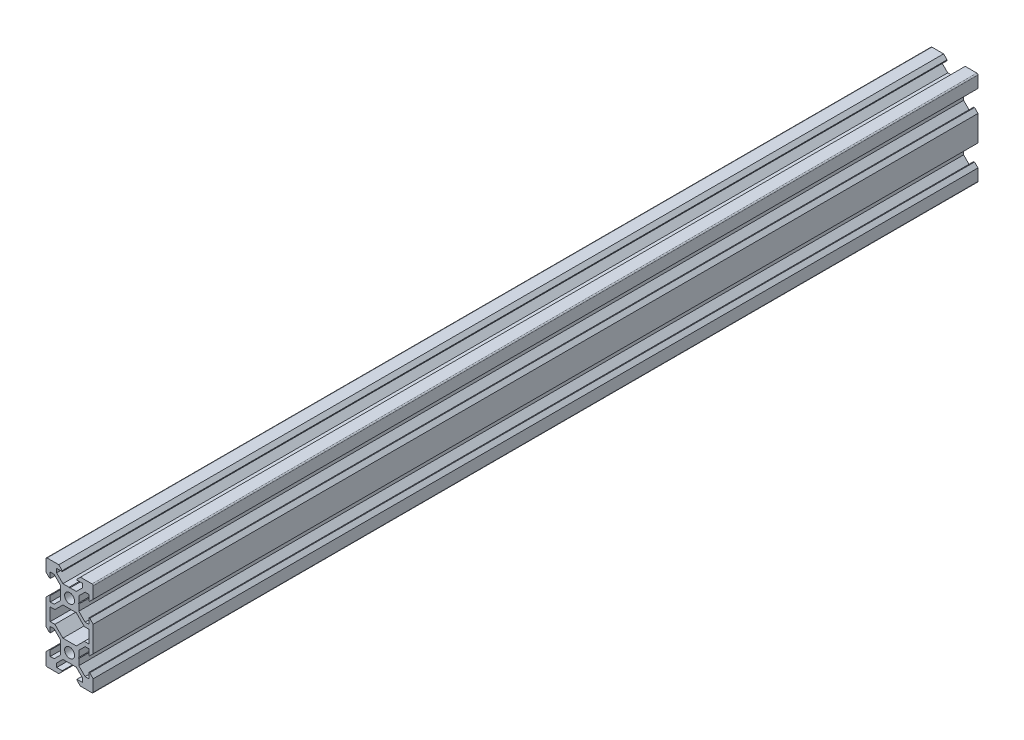
SolidWorks part; units mm, degrees
material "6061-T6 (SS)"
ref_plane "Front Plane" through (0, 0, 0) normal (0, 0, 1) x (1, 0, 0)
ref_plane "Top Plane" through (0, 0, 0) normal (0, 1, 0) x (1, 0, 0)
ref_plane "Right Plane" through (0, 0, 0) normal (1, 0, 0) x (0, 0, -1)
sketch "Sketch1" plane through (0, 0, 0) normal (0, 0, 1) x (1, 0, 0)
  line L0 (0, 0) -> (10, 0) construction
  line L1 (9.5, -20) -> (-9.5, -20)
  line L2 (10, -19.5) -> (10, 19.5)
  line L3 (9.5, 20) -> (-9.5, 20)
  line L4 (-10, -19.5) -> (-10, 19.5)
  line L5 (10, -20) -> (-10, 20) construction
  line L6 (10, 20) -> (-10, -20) construction
  circle A0 centre (0, 10) radius 2.1
  circle A1 centre (0, -10) radius 2.1
  arc A2 (-9.5, -20) -> (-10, -19.5) centre (-9.5, -19.5) cw
  arc A3 (9.5, -20) -> (10, -19.5) centre (9.5, -19.5) ccw
  arc A4 (10, 19.5) -> (9.5, 20) centre (9.5, 19.5) ccw
  arc A5 (-9.5, 20) -> (-10, 19.5) centre (-9.5, 19.5) ccw
  point P0 (0, 0)
  line B0 (0, 10) -> (0, 20) construction
  line B1 (0, 13.69) -> (-0.21, 13.9)
  line B2 (-0.21, 13.9) -> (-2.8393, 13.9)
  line B3 (-2.8393, 13.9) -> (-5.5, 16.5607)
  line B4 (-5.5, 16.5607) -> (-5.5, 18.2)
  line B5 (-5.5, 18.2) -> (-3.125, 18.2)
  line B6 (-3.125, 18.2) -> (-3.125, 18.545)
  line B7 (-3.125, 18.545) -> (-4.58, 20)
  line B8 (-4.58, 20) -> (4.58, 20)
  line B9 (0, 10) -> (-5.9132, 15.9132) construction
  line B10 (3.125, 18.545) -> (4.58, 20)
  line B11 (3.125, 18.2) -> (3.125, 18.545)
  line B12 (5.5, 18.2) -> (3.125, 18.2)
  line B13 (5.5, 16.5607) -> (5.5, 18.2)
  line B14 (2.8393, 13.9) -> (5.5, 16.5607)
  line B15 (0.21, 13.9) -> (2.8393, 13.9)
  line B16 (0, 13.69) -> (0.21, 13.9)
  line B17 (0, 10) -> (-10, 10) construction
  line B18 (-3.69, 10) -> (-3.9, 9.79)
  line B19 (-3.9, 9.79) -> (-3.9, 7.1607)
  line B20 (-3.9, 7.1607) -> (-6.5607, 4.5)
  line B21 (-6.5607, 4.5) -> (-8.2, 4.5)
  line B22 (-8.2, 4.5) -> (-8.2, 6.875)
  line B23 (-8.2, 6.875) -> (-8.545, 6.875)
  line B24 (-8.545, 6.875) -> (-10, 5.42)
  line B25 (-10, 5.42) -> (-10, 14.58)
  line B26 (0, 10) -> (-5.9132, 4.0868) construction
  line B27 (-8.545, 13.125) -> (-10, 14.58)
  line B28 (-8.2, 13.125) -> (-8.545, 13.125)
  line B29 (-8.2, 15.5) -> (-8.2, 13.125)
  line B30 (-6.5607, 15.5) -> (-8.2, 15.5)
  line B31 (-3.9, 12.8393) -> (-6.5607, 15.5)
  line B32 (-3.9, 10.21) -> (-3.9, 12.8393)
  line B33 (-3.69, 10) -> (-3.9, 10.21)
  line B34 (0, -10) -> (-10, -10) construction
  line B35 (-3.69, -10) -> (-3.9, -10.21)
  line B36 (-3.9, -10.21) -> (-3.9, -12.8393)
  line B37 (-3.9, -12.8393) -> (-6.5607, -15.5)
  line B38 (-6.5607, -15.5) -> (-8.2, -15.5)
  line B39 (-8.2, -15.5) -> (-8.2, -13.125)
  line B40 (-8.2, -13.125) -> (-8.545, -13.125)
  line B41 (-8.545, -13.125) -> (-10, -14.58)
  line B42 (-10, -14.58) -> (-10, -5.42)
  line B43 (0, -10) -> (-5.9132, -15.9132) construction
  line B44 (-8.545, -6.875) -> (-10, -5.42)
  line B45 (-8.2, -6.875) -> (-8.545, -6.875)
  line B46 (-8.2, -4.5) -> (-8.2, -6.875)
  line B47 (-6.5607, -4.5) -> (-8.2, -4.5)
  line B48 (-3.9, -7.1607) -> (-6.5607, -4.5)
  line B49 (-3.9, -9.79) -> (-3.9, -7.1607)
  line B50 (-3.69, -10) -> (-3.9, -9.79)
  line B51 (0, -10) -> (0, -20) construction
  line B52 (0, -13.69) -> (0.21, -13.9)
  line B53 (0.21, -13.9) -> (2.8393, -13.9)
  line B54 (2.8393, -13.9) -> (5.5, -16.5607)
  line B55 (5.5, -16.5607) -> (5.5, -18.2)
  line B56 (5.5, -18.2) -> (3.125, -18.2)
  line B57 (3.125, -18.2) -> (3.125, -18.545)
  line B58 (3.125, -18.545) -> (4.58, -20)
  line B59 (4.58, -20) -> (-4.58, -20)
  line B60 (0, -10) -> (5.9132, -15.9132) construction
  line B61 (-3.125, -18.545) -> (-4.58, -20)
  line B62 (-3.125, -18.2) -> (-3.125, -18.545)
  line B63 (-5.5, -18.2) -> (-3.125, -18.2)
  line B64 (-5.5, -16.5607) -> (-5.5, -18.2)
  line B65 (-2.8393, -13.9) -> (-5.5, -16.5607)
  line B66 (-0.21, -13.9) -> (-2.8393, -13.9)
  line B67 (0, -13.69) -> (-0.21, -13.9)
  line B68 (0, -10) -> (10, -10) construction
  line B69 (3.69, -10) -> (3.9, -9.79)
  line B70 (3.9, -9.79) -> (3.9, -7.1607)
  line B71 (3.9, -7.1607) -> (6.5607, -4.5)
  line B72 (6.5607, -4.5) -> (8.2, -4.5)
  line B73 (8.2, -4.5) -> (8.2, -6.875)
  line B74 (8.2, -6.875) -> (8.545, -6.875)
  line B75 (8.545, -6.875) -> (10, -5.42)
  line B76 (10, -5.42) -> (10, -14.58)
  line B77 (0, -10) -> (5.9132, -4.0868) construction
  line B78 (8.545, -13.125) -> (10, -14.58)
  line B79 (8.2, -13.125) -> (8.545, -13.125)
  line B80 (8.2, -15.5) -> (8.2, -13.125)
  line B81 (6.5607, -15.5) -> (8.2, -15.5)
  line B82 (3.9, -12.8393) -> (6.5607, -15.5)
  line B83 (3.9, -10.21) -> (3.9, -12.8393)
  line B84 (3.69, -10) -> (3.9, -10.21)
  line B85 (0, 10) -> (10, 10) construction
  line B86 (3.69, 10) -> (3.9, 10.21)
  line B87 (3.9, 10.21) -> (3.9, 12.8393)
  line B88 (3.9, 12.8393) -> (6.5607, 15.5)
  line B89 (6.5607, 15.5) -> (8.2, 15.5)
  line B90 (8.2, 15.5) -> (8.2, 13.125)
  line B91 (8.2, 13.125) -> (8.545, 13.125)
  line B92 (8.545, 13.125) -> (10, 14.58)
  line B93 (10, 14.58) -> (10, 5.42)
  line B94 (0, 10) -> (5.9132, 15.9132) construction
  line B95 (8.545, 6.875) -> (10, 5.42)
  line B96 (8.2, 6.875) -> (8.545, 6.875)
  line B97 (8.2, 4.5) -> (8.2, 6.875)
  line B98 (6.5607, 4.5) -> (8.2, 4.5)
  line B99 (3.9, 7.1607) -> (6.5607, 4.5)
  line B100 (3.9, 9.79) -> (3.9, 7.1607)
  line B101 (3.69, 10) -> (3.9, 9.79)
  line B102 (-8.2, -2.7) -> (-8.2, 2.7)
  line B103 (-8.2, 2.7) -> (-6.2393, 2.7)
  line B104 (-6.2393, 2.7) -> (-2.8393, 6.1)
  line B105 (-2.8393, 6.1) -> (2.8393, 6.1)
  line B106 (0, 6.1) -> (0, 0) construction
  line B107 (0, 0) -> (-8.2, 0) construction
  line B108 (6.2393, 2.7) -> (2.8393, 6.1)
  line B109 (8.2, 2.7) -> (6.2393, 2.7)
  line B110 (8.2, -2.7) -> (8.2, 2.7)
  line B111 (8.2, -2.7) -> (6.2393, -2.7)
  line B112 (6.2393, -2.7) -> (2.8393, -6.1)
  line B113 (-2.8393, -6.1) -> (2.8393, -6.1)
  line B114 (-6.2393, -2.7) -> (-2.8393, -6.1)
  line B115 (-8.2, -2.7) -> (-6.2393, -2.7)
  line B116 (0, 6.1) -> (0, 10) construction
  line B117 (0, 10) -> (-5.0927, 4.9073) construction
  dimension "D4" = 4.2
  dimension "D5" = 0.5
  dimension "D1" = 20
  dimension "D2" = 40
  dimension "D3" = 20
sketch_block_instance "V Slot 1-4"
sketch_block "V Slot 1" parameters "D1"=10, "D2"=11, "D3"=4.3, "D4"=1.8, "D5"=0.21, "D6"=45, "D7"=9.16, "D8"=1.5, "D9"=6.25
sketch_block_instance "V Slot 1-5"
sketch_block_instance "V Slot 1-6"
sketch_block_instance "V Slot 1-7"
sketch_block_instance "V Slot 1-8"
sketch_block_instance "V Slot 1-9"
sketch_block_instance "Center Cutout 1-1"
sketch_block "Center Cutout 1" parameters "D1"=5.4, "D2"=12.2, "D3"=8.2, "D4"=45, "D5"=10, "D6"=1.5
extrude "Boss-Extrude1" add sketch "Sketch1" along normal blind 375 contours B101 B86 B87 B88 B89 B90 B91 B92 L2 A4 L3 B10 B11 B12 B13 B14 B15 B16 B1 B2 B3 B4 B5 B6 B7 A5 L4 B27 B28 B29 B30 B31 B32 B33 B18 B19 B20 B21 B22 B23 B24 B44 B45 B46 B47 B48 B49 B50 B35
